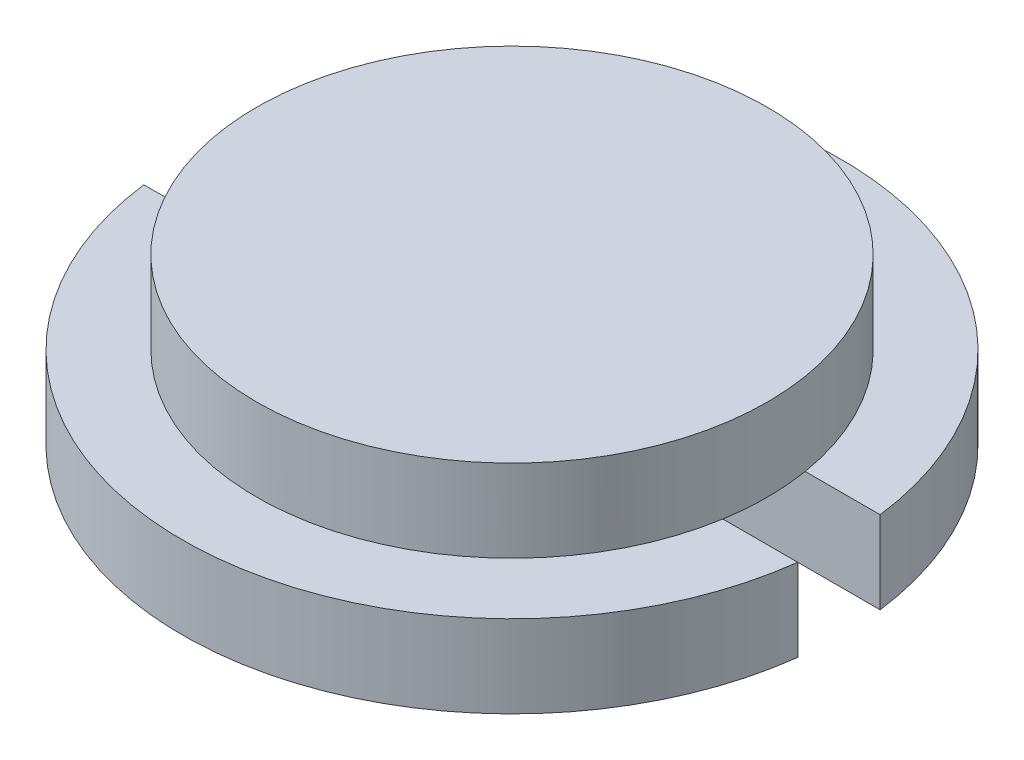
SolidWorks part; units mm, degrees
material "PBT General Purpose"
ref_plane "Front Plane" through (0, 0, 0) normal (0, 0, 1) x (1, 0, 0)
ref_plane "Top Plane" through (0, 0, 0) normal (0, 1, 0) x (1, 0, 0)
ref_plane "Right Plane" through (0, 0, 0) normal (1, 0, 0) x (0, 0, -1)
sketch "Sketch1" plane through (0, 0, 0) normal (0, 1, 0) x (1, 0, 0)
  circle A0 centre (0, 0) radius 31
extrude "Boss-Extrude1" add sketch "Sketch1" along normal blind 10
sketch "Sketch6" plane through (0, 0, 0) normal (0, -1, 0) x (-1, 0, 0)
  line L0 (0, 0) -> (15, 0) construction
  line L1 (0, 0) -> (-15, 0) construction
  line L2 (15, 0) -> (15, -10)
  line L3 (15, -10) -> (-15, -10)
  line L4 (-15, -10) -> (-15, 0)
  line L5 (-15, 0) -> (-15, 10)
  line L6 (-15, 10) -> (15, 10)
  line L7 (15, 10) -> (15, 0)
extrude "Boss-Extrude3" add sketch "Sketch6" along normal blind 10
sketch "Sketch7" plane through (0, 0, -10) normal (0, 0, -1) x (-1, 0, 0)
  line L0 (0, 0) -> (0, -10) construction
  line L1 (15, -10) -> (-15, -10) construction
  line L2 (10, -5) -> (5, -5)
  line L3 (10, -5) -> (15, -10)
  line L4 (5, -5) -> (5, 0)
  line L5 (15, 0) -> (-15, 0) construction
  line L6 (5, 0) -> (15, 0)
  line L7 (15, 0) -> (15, -10)
  line L8 (-5, 0) -> (-15, 0)
  line L9 (-5, -5) -> (-5, 0)
  line L10 (-10, -5) -> (-15, -10)
  line L11 (-10, -5) -> (-5, -5)
  line L12 (-15, 0) -> (-15, -10)
  line L13 (5, 0) -> (-5, 0) construction
extrude "Cut-Extrude2" cut sketch "Sketch7" against normal blind 20
sketch "Sketch8" plane through (0, 0, 0) normal (0, -1, 0) x (1, 0, 0)
  line L0 (15, -10) -> (22.5, -10)
  line L1 (-15, -10) -> (-22.5, -10)
  line L3 (15, 10) -> (22.5, 10)
  line L4 (22.5, 10) -> (22.5, -10)
  line L5 (-22.5, -10) -> (-22.5, 10)
  line L6 (-22.5, 10) -> (-15, 10)
  line L7 (15, 10) -> (-15, 10)
  line L8 (15, -10) -> (-15, -10)
  circle A0 centre (0, 0) radius 40
extrude "Boss-Extrude4" add sketch "Sketch8" along normal blind 10
sketch "Sketch9" plane through (0, -10, 0) normal (0, -1, 0) x (1, 0, 0)
  line L0 (0, 0) -> (40, 0) construction
  line L1 (0, 0) -> (0, 5)
  line L2 (0, 5) -> (22.5, 5)
  line L3 (22.5, -10) -> (22.5, 10) construction
  line L4 (22.5, 5) -> (22.5, 10)
  line L5 (22.5, 10) -> (-22.5, 10)
  line L6 (0, 5) -> (-22.5, 5)
  line L7 (-22.5, 10) -> (-22.5, -10) construction
  line L8 (-22.5, 5) -> (-22.5, 10)
  line L9 (0, 0) -> (0, -5) construction
  line L10 (0, -5) -> (22.5, -5)
  line L11 (22.5, -10) -> (22.5, 10) construction
  line L12 (22.5, -5) -> (22.5, -10)
  line L13 (22.5, -10) -> (-22.5, -10)
  line L14 (-22.5, -10) -> (-22.5, -5)
  line L15 (-22.5, -5) -> (0, -5)
  circle A0 centre (0, 0) radius 40 construction
  line M6 (-22.5, 10) -> (-15, 10)
  line M7 (-15, 10) -> (-15, -10)
  line M8 (-15, -10) -> (-22.5, -10)
  line M9 (-22.5, -10) -> (-22.5, 10)
  line M10 (15, -10) -> (15, 10)
  line M11 (15, 10) -> (22.5, 10)
  line M12 (22.5, 10) -> (22.5, -10)
  line M13 (22.5, -10) -> (15, -10)
extrude "Boss-Extrude5" add sketch "Sketch9" against normal blind 10 contours L6 M7 M6 M9 | L2 M10 M12 M11 | L10 M10 M13 M12 | L15 M9 M8 M7 | L6 L2 L5 M10 M7 | L15 L13 L10 M7 M10
sketch "Sketch10" plane through (0, -10, 0) normal (0, -1, 0) x (1, 0, 0)
  line L0 (-22.5, -5) -> (-39.6863, -5)
  line L1 (-39.6863, -5) -> (-48.1805, -5)
  line L2 (-48.1805, -5) -> (-48.1805, 5)
  line L3 (-22.5, 5) -> (-48.1805, 5)
  line L4 (0, 0) -> (0, 14.4924) construction
  line L5 (22.5, 5) -> (48.1805, 5)
  line L6 (48.1805, -5) -> (48.1805, 5)
  line L7 (39.6863, -5) -> (48.1805, -5)
  line L8 (22.5, -5) -> (39.6863, -5)
  line L9 (-22.5, 5) -> (-22.5, -5)
  line L10 (22.5, 5) -> (22.5, -5)
  circle A0 centre (0, 0) radius 40 construction
extrude "Cut-Extrude3" cut sketch "Sketch10" against normal blind 10
